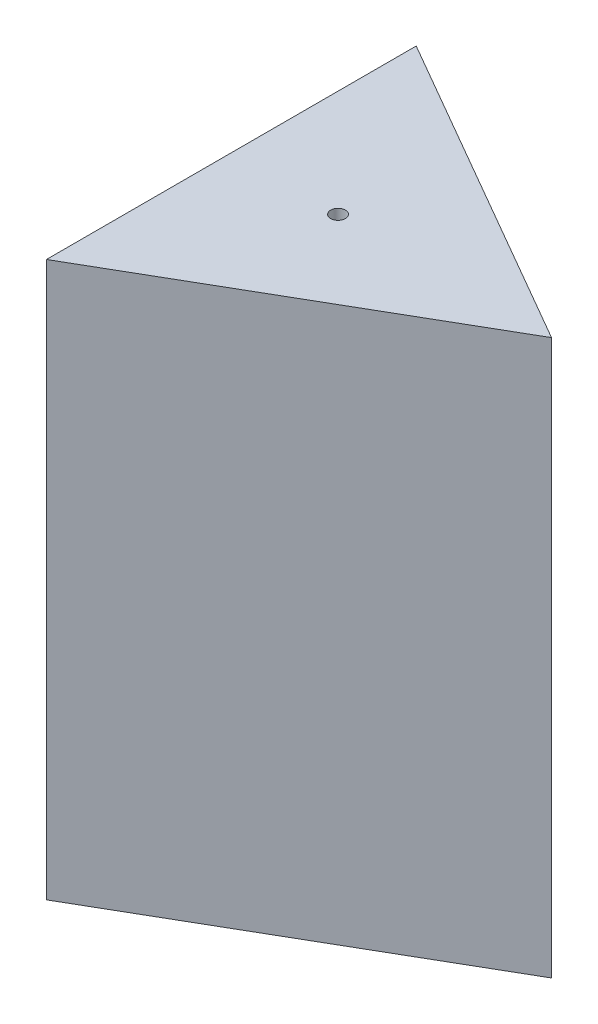
SolidWorks part; units mm, degrees
ref_plane "Front Plane" through (0, 0, 0) normal (0, 0, 1) x (1, 0, 0)
ref_plane "Top Plane" through (0, 0, 0) normal (0, 1, 0) x (1, 0, 0)
ref_plane "Right Plane" through (0, 0, 0) normal (1, 0, 0) x (0, 0, -1)
sketch "Sketch1" plane through (0, 0, 0) normal (0, 1, 0) x (1, 0, 0)
  line L1 (115.4701, 0) -> (-57.735, 100)
  line L2 (-57.735, 100) -> (-57.735, -100)
  line L3 (-57.735, -100) -> (115.4701, 0)
  circle A0 centre (0, 0) radius 57.735 construction
  dimension "D1" = 200
extrude "Boss-Extrude2" add sketch "Sketch1" along normal blind 300
sketch "Sketch3" plane through (0, 0, 0) normal (0, -1, 0) x (1, 0, 0)
  circle A0 centre (0, 0) radius 4
extrude "Cut-Extrude2" cut sketch "Sketch3" against normal blind 300
